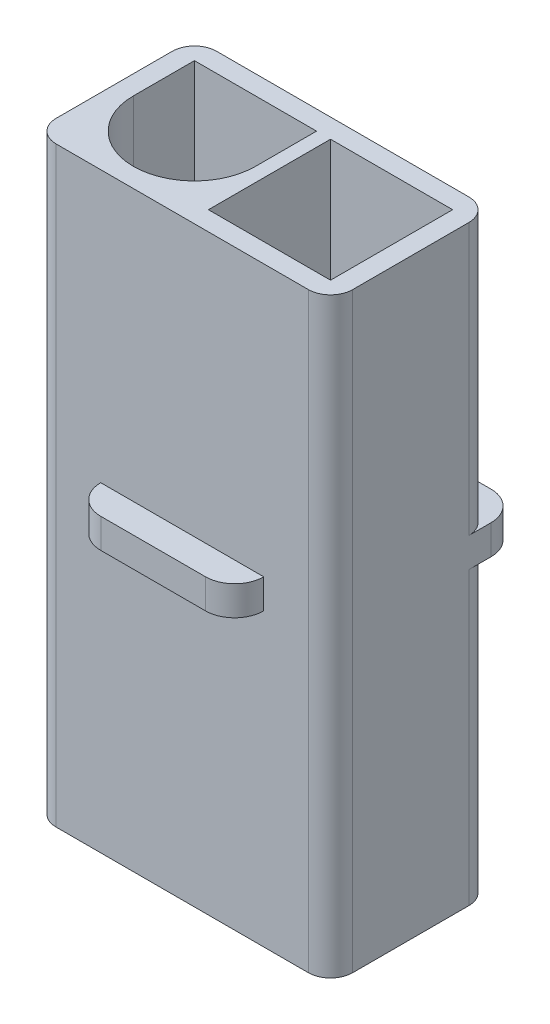
SolidWorks part; units mm, degrees
ref_plane "Front Plane" through (0, 0, 0) normal (0, 0, 1) x (1, 0, 0)
ref_plane "Top Plane" through (0, 0, 0) normal (0, 1, 0) x (1, 0, 0)
ref_plane "Right Plane" through (0, 0, 0) normal (1, 0, 0) x (0, 0, -1)
sketch "Sketch1" plane through (0, 0, 0) normal (0, 1, 0) x (1, 0, 0)
  line L1 (-6.68, -3.615) -> (6.68, -3.615)
  line L2 (-6.68, -3.615) -> (-6.68, 3.615)
  line L3 (-6.68, 3.615) -> (6.68, 3.615)
  line L4 (6.68, -3.615) -> (6.68, 3.615)
  line L5 (-6.68, -3.615) -> (6.68, 3.615) construction
  line L6 (-6.68, 3.615) -> (6.68, -3.615) construction
  point P0 (0, 0)
  dimension "D1" = 7.23
  dimension "D2" = 13.36
extrude "Boss-Extrude1" add sketch "Sketch1" along normal mid plane 26.65
sketch "Sketch2" plane through (0, 13.325, 0) normal (0, 1, 0) x (1, 0, 0)
  line L0 (-5.815, 2.75) -> (-0.315, 2.75)
  line L1 (-0.315, 2.75) -> (-0.315, 0)
  line L2 (-5.815, 0) -> (-5.815, 2.75)
  line L3 (5.815, 0) -> (6.68, 0) construction
  line L4 (0.315, 2.75) -> (5.815, 2.75)
  line L5 (0.315, 2.75) -> (0.315, -2.75)
  line L6 (0.315, -2.75) -> (5.815, -2.75)
  line L7 (5.815, 2.75) -> (5.815, -2.75)
  line L8 (6.68, -3.615) -> (6.68, 3.615) construction
  line L9 (5.815, 2.75) -> (5.815, 3.615) construction
  line L10 (6.68, 3.615) -> (-6.68, 3.615) construction
  line L11 (-5.815, 2.75) -> (-6.68, 2.75) construction
  line L12 (-6.68, 3.615) -> (-6.68, -3.615) construction
  arc A0 (-0.315, 0) -> (-5.815, 0) centre (-3.065, 0) cw
  dimension "D1" = 5.5
  dimension "D2" = 0.865
extrude "Cut-Extrude1" cut sketch "Sketch2" against normal blind 10
sketch "Sketch3" plane through (0, -13.325, 0) normal (0, -1, 0) x (1, 0, 0)
  line L0 (-3.065, 0) -> (3.065, 0) construction
  circle A1 centre (-3.065, 0) radius 2.75
  arc A2 (-0.315, 0) -> (-5.815, 0) centre (-3.065, 0) ccw construction
  circle A3 centre (3.065, 0) radius 2.75
  dimension "D1" = 5.5
extrude "Cut-Extrude2" cut sketch "Sketch3" against normal blind 11.75
sketch "Sketch4" plane through (0, 0, 0) normal (1, 0, 0) x (0, 0, -1)
  line L0 (3.615, 13.325) -> (5.145, 10.975)
  line L1 (5.145, 10.975) -> (3.615, 10.975)
  line L2 (3.615, 13.325) -> (3.615, -13.325) construction
  line L3 (3.615, 10.975) -> (3.615, 13.325)
  line L4 (-3.615, 13.325) -> (-3.615, -13.325) construction
  dimension "D1" = 2.35
  dimension "D2" = 8.76
extrude "Boss-Extrude2" add sketch "Sketch4" along normal mid plane 3.6
ref_plane "Plane1" through (0, -0.215, 0) normal (0, 1, 0) x (1, 0, 0)
sketch "Sketch5" plane through (0, -0.215, 0) normal (0, 1, 0) x (1, 0, 0)
  line L0 (-5.37, 4.925) -> (-4.56, 4.925)
  line L1 (4.56, 4.925) -> (5.37, 4.925)
  line L2 (-2.36, -4.925) -> (2.36, -4.925)
  line L3 (-1.8, 3.615) -> (-6.68, 3.615) construction
  line L4 (6.68, 3.615) -> (1.8, 3.615) construction
  line L5 (-6.68, -3.615) -> (6.68, -3.615) construction
  line L6 (-6.68, 3.615) -> (-3.25, 3.615)
  line L7 (3.25, 3.615) -> (6.68, 3.615)
  line L8 (3.67, -3.615) -> (-3.67, -3.615)
  line L9 (-5.37, 4.925) -> (-5.37, 3.615) construction
  line L10 (-2.36, -3.615) -> (-2.36, -4.925) construction
  line L11 (-6.68, 3.615) -> (-6.68, -3.615) construction
  line L12 (6.68, -3.615) -> (6.68, 3.615) construction
  arc A0 (-4.56, 4.925) -> (-3.25, 3.615) centre (-4.56, 3.615) cw
  arc A1 (-5.37, 4.925) -> (-6.68, 3.615) centre (-5.37, 3.615) ccw
  arc A2 (4.56, 4.925) -> (3.25, 3.615) centre (4.56, 3.615) ccw
  arc A3 (5.37, 4.925) -> (6.68, 3.615) centre (5.37, 3.615) cw
  arc A4 (2.36, -4.925) -> (3.67, -3.615) centre (2.36, -3.615) ccw
  arc A5 (-2.36, -4.925) -> (-3.67, -3.615) centre (-2.36, -3.615) cw
  point P24 (0, -3.615)
  point P25 (0, 0)
  point P26 (0, 0)
  point P29 (0, 0)
  dimension "D1" = 3.43
  dimension "D2" = 1.31
  dimension "D3" = 7.34
extrude "Boss-Extrude3" add sketch "Sketch5" along normal blind 1.33
fillet "Fillet1" radius 1 6 edges at (6.68, 7.22, -3.615) (-6.68, 7.22, -3.615) (6.68, 0, 3.615) (-6.68, 0, 3.615) (6.68, -6.77, -3.615) (-6.68, -6.77, -3.615)
